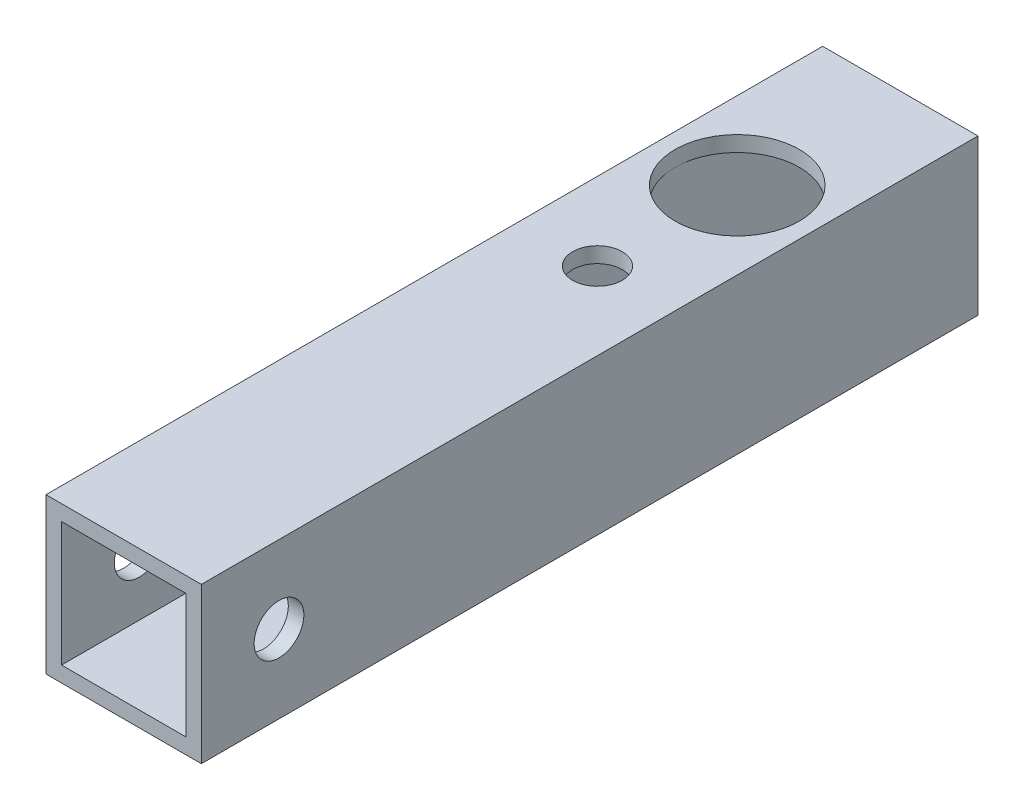
SolidWorks part; units mm, degrees
material "1060 合金"
ref_plane "正面" through (0, 0, 0) normal (0, 0, 1) x (1, 0, 0)
ref_plane "平面" through (0, 0, 0) normal (0, 1, 0) x (1, 0, 0)
ref_plane "右側面" through (0, 0, 0) normal (1, 0, 0) x (0, 0, -1)
sketch "ｽｹｯﾁ1" plane through (0, 0, 0) normal (0, 0, 1) x (1, 0, 0)
  line L1 (0, 0) -> (10, 0)
  line L2 (0, 0) -> (0, 10)
  line L3 (0, 10) -> (10, 10)
  line L4 (10, 0) -> (10, 10)
  dimension "D1" = 10
extrude "押し出し-薄板1" add sketch "ｽｹｯﾁ1" along normal blind 50 thin thin type one direction reverse wall 1
sketch "ｽｹｯﾁ2" plane through (0, 10, 0) normal (0, 1, 0) x (1, 0, 0)
  line L0 (5, 0) -> (5, -50) construction
  line L1 (10, 0) -> (0, 0) construction
  line L2 (10, -50) -> (0, -50) construction
  circle A1 centre (5, -10.5) radius 4
  circle A2 centre (5, -19.5) radius 1.6
  dimension "D1" = 3.2
  dimension "D2" = 8
  dimension "D3" = 10.5
  dimension "D5" = 9
extrude "ｶｯﾄ - 押し出し1" cut sketch "ｽｹｯﾁ2" against normal through all
sketch "ｽｹｯﾁ4" plane through (0, 0, 0) normal (0, -1, 0) x (1, 0, 0)
  circle A1 centre (5, 19.5) radius 2.6
  dimension "D1" = 5.2
extrude "ｶｯﾄ - 押し出し2" cut sketch "ｽｹｯﾁ4" against normal up to next
sketch "ｽｹｯﾁ5" plane through (10, 0, 0) normal (1, 0, 0) x (0, 0, -1)
  line L0 (-50, 5) -> (0, 5) construction
  line L1 (-50, 0) -> (-50, 10) construction
  line L2 (0, 0) -> (0, 10) construction
  circle A0 centre (-45, 5) radius 1.6
  dimension "D1" = 3.2
  dimension "D2" = 5
extrude "ｶｯﾄ - 押し出し3" cut sketch "ｽｹｯﾁ5" against normal through all
